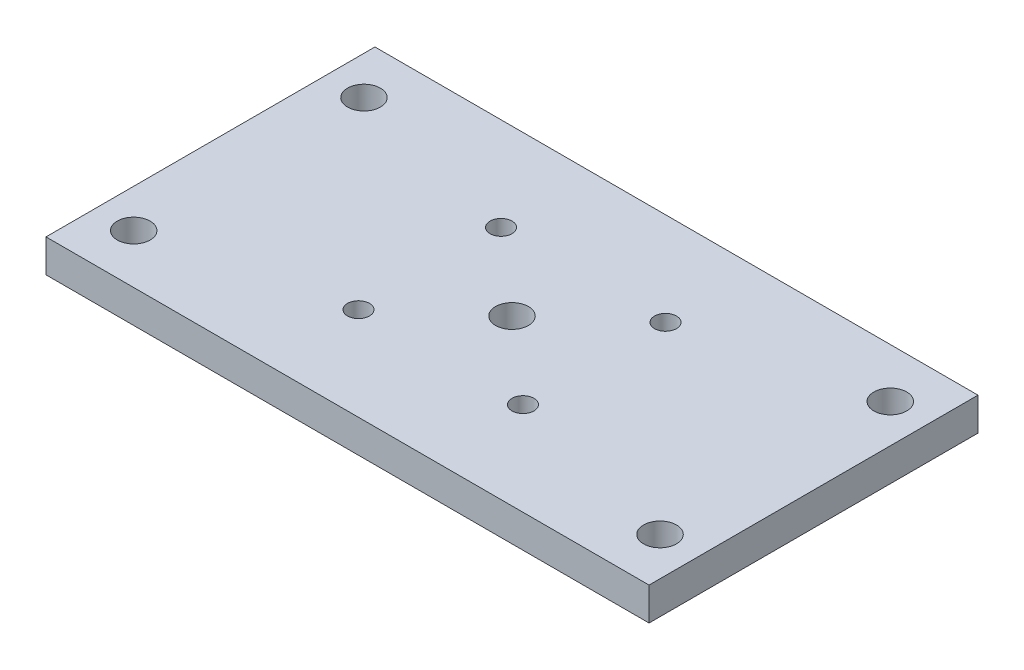
SolidWorks part; units mm, degrees
ref_plane "Plan de face" through (0, 0, 0) normal (0, 0, 1) x (1, 0, 0)
ref_plane "Plan de dessus" through (0, 0, 0) normal (0, 1, 0) x (1, 0, 0)
ref_plane "Plan de droite" through (0, 0, 0) normal (1, 0, 0) x (0, 0, -1)
sketch "Esquisse1" plane through (0, 0, 0) normal (0, 1, 0) x (1, 0, 0)
  line L0 (0, 15) -> (0, 0) construction
  line L1 (-27.5, -15) -> (27.5, -15)
  line L2 (-27.5, -15) -> (-27.5, 15)
  line L3 (-27.5, 15) -> (27.5, 15)
  line L4 (27.5, -15) -> (27.5, 15)
  line L5 (0, 0) -> (-27.5, 0) construction
  circle A0 centre (-7.5, 6.5) radius 1
  circle A1 centre (-24, 10.5) radius 1.5
  circle A2 centre (24, 10.5) radius 1.5
  circle A3 centre (7.5, 6.5) radius 1
  circle A4 centre (7.5, -6.5) radius 1
  circle A5 centre (24, -10.5) radius 1.5
  circle A6 centre (-24, -10.5) radius 1.5
  circle A7 centre (-7.5, -6.5) radius 1
  circle A8 centre (0, 0) radius 1.5
  dimension "D1" = 3
  dimension "D2" = 2
  dimension "D3" = 15
  dimension "D4" = 13
  dimension "D6" = 4.5
  dimension "D7" = 3.5
  dimension "D8" = 48
  dimension "D9" = 21
  dimension "D5" = 30
  dimension "D10" = 55
extrude "Boss.-Extru.1" add sketch "Esquisse1" along normal blind 3
